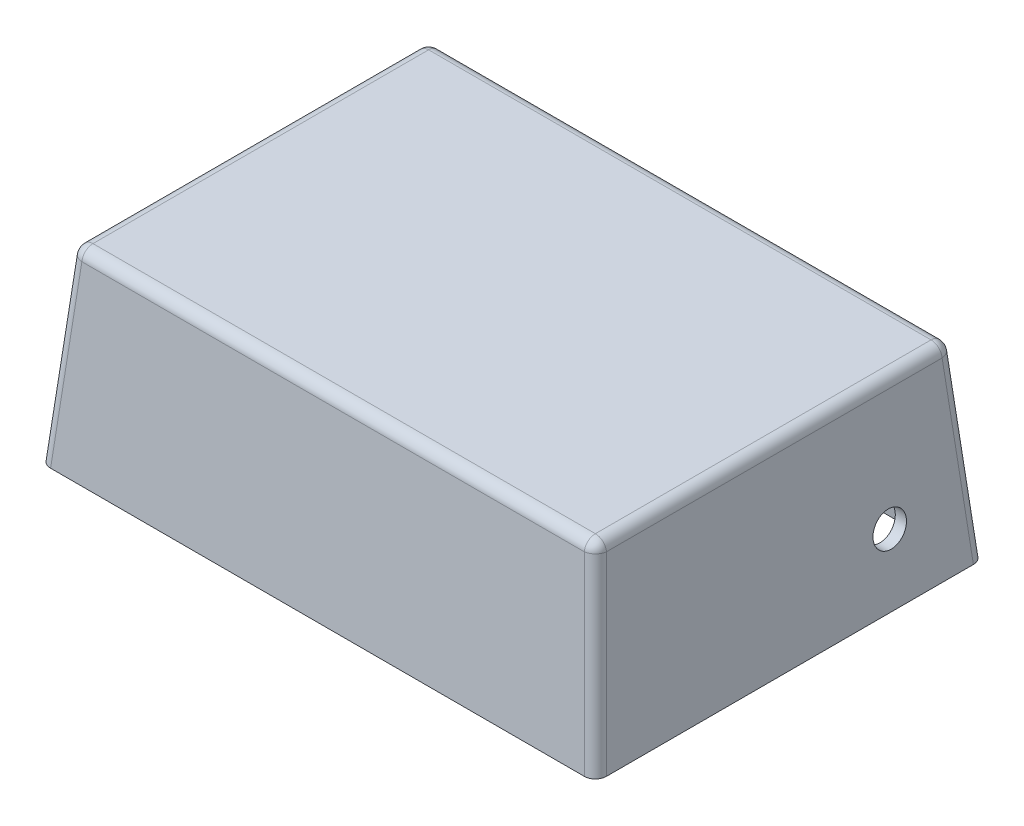
SolidWorks part; units mm, degrees
ref_plane "Plan de face" through (0, 0, 0) normal (0, 0, 1) x (1, 0, 0)
ref_plane "Plan de dessus" through (0, 0, 0) normal (0, 1, 0) x (1, 0, 0)
ref_plane "Plan de droite" through (0, 0, 0) normal (1, 0, 0) x (0, 0, -1)
sketch "Esquisse1" plane through (0, 0, 0) normal (0, 0, 1) x (1, 0, 0)
  line L1 (-25, 17) -> (25, 17)
  line L2 (-25, 17) -> (-25, 0)
  line L3 (-25, 0) -> (25, 0)
  line L4 (25, 17) -> (25, 0)
  dimension "D1" = 25
  dimension "D2" = 50
  dimension "D3" = 17
extrude "Boss.-Extru.1" add sketch "Esquisse1" along normal blind 35
draft "Dépouille2" type of draft neutral plane draft angle 5 faces to draft 4 face at (0, 8.5, 0) face at (25, 8.5, 17.5) face at (-25, 8.5, 17.5) face at (0, 8.5, 35) neutral plane through (-25, 0, 35) neutral plane normal (0, -1, 0) reverse direction yes parameters "D1"=5
shell "Coque2" thickness 1
fillet "Congé1" radius 1 16 edges at (23.5127, 17, 17.5) (0, 17, 33.5127) (-23.5127, 17, 17.5) (0, 17, 1.4873) (-24.2563, 8.5, 34.2563) (24.2563, 8.5, 0.7437) (-24.2563, 8.5, 0.7437) (24.2563, 8.5, 34.2563) (-22.5964, 16, 17.5) (0, 16, 32.5964) (22.5964, 16, 17.5) (0, 16, 2.4036) (-23.2963, 8, 33.2963) (-23.2963, 8, 1.7037) (23.2963, 8, 1.7037) (23.2963, 8, 33.2963)
sketch "Esquisse2" plane through (0, 16, 0) normal (0, -1, 0) x (-1, 0, 0)
  circle A0 centre (-19.25, -29.25) radius 1
  circle A1 centre (19.25, -5.75) radius 1
  circle A2 centre (-19.25, -29.25) radius 2
  circle A3 centre (19.25, -5.75) radius 2
  dimension "D1" = 19.25
  dimension "D2" = 19.25
  dimension "D3" = 23.5
  dimension "D4" = 5.75
  dimension "D5" = 1
extrude "Boss.-Extru.2" add sketch "Esquisse2" along normal blind 14.5
sketch "Esquisse3" plane through (0, 0, 0) normal (1, 0, 0) x (0, 0, -1)
  line L0 (-34.0038, 0) -> (-0.9962, 0) construction
  line L1 (-20, 5) -> (-20, -1)
  line L2 (-20, -1) -> (-15, -1)
  line L3 (-15, -1) -> (-15, 5)
  arc A0 (-15, 5) -> (-20, 5) centre (-17.5, 5) ccw
  dimension "D1" = 5
extrude "Enlèv. mat.-Extru.1" cut sketch "Esquisse3" against normal up to next
sketch "Esquisse4" plane through (0, 0, 0) normal (1, 0, 0) x (0, 0, -1)
  line L0 (-34.0038, 0) -> (-0.9962, 0) construction
  circle A0 centre (-8, 6) radius 1.5
  dimension "D1" = 6
  dimension "D2" = 8
extrude "Enlèv. mat.-Extru.2" cut sketch "Esquisse4" along normal up to next
